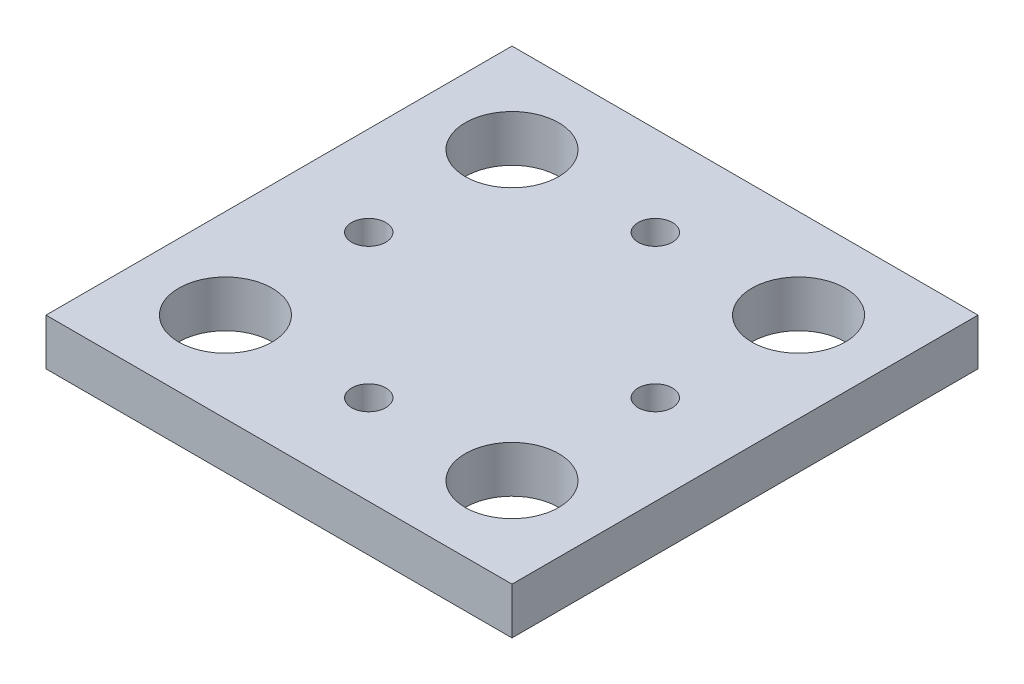
SolidWorks part; units mm, degrees
material "polylactic acid(PLA)(20%)"
ref_plane "Front Plane" through (0, 0, 0) normal (0, 0, 1) x (1, 0, 0)
ref_plane "Top Plane" through (0, 0, 0) normal (0, 1, 0) x (1, 0, 0)
ref_plane "Right Plane" through (0, 0, 0) normal (1, 0, 0) x (0, 0, -1)
sketch "Sketch1" plane through (0, 0, 0) normal (0, 1, 0) x (1, 0, 0)
  line L1 (-50, 50) -> (50, 50)
  line L2 (-50, 50) -> (-50, -50)
  line L3 (-50, -50) -> (50, -50)
  line L4 (50, 50) -> (50, -50)
  point P4 (50, 0)
  point P7 (0, -50)
  dimension "D1" = 100
extrude "Boss-Extrude1" add sketch "Sketch1" along normal blind 10
sketch "Sketch3" plane through (0, 0, 0) normal (0, 1, 0) x (1, 0, 0)
  line L0 (50, 50) -> (-50, 50) construction
  line L1 (-50, 50) -> (-50, -50) construction
  circle A0 centre (-30.7468, 30.7468) radius 10.025
  circle A1 centre (30.7468, 30.7468) radius 10.025
  circle A2 centre (30.7468, -30.7468) radius 10.025
  circle A3 centre (-30.7468, -30.7468) radius 10.025
  circle A4 centre (-30.7468, 30.7468) radius 19.2532 construction
  circle A5 centre (-30.7468, -30.7468) radius 19.2532 construction
  circle A6 centre (30.7468, 30.7468) radius 19.2532 construction
  circle A7 centre (0, 30.7468) radius 3.675
  circle A8 centre (0, 30.7468) radius 7.5 construction
  circle A9 centre (30.7468, 0) radius 3.675
  circle A10 centre (0, -30.7468) radius 3.675
  circle A11 centre (-30.7468, 0) radius 3.675
  point P14 (0, 0)
  point P29 (0, 0)
  dimension "D1" = 20.05
  dimension "D2" = 38.5064
  dimension "D4" = 7.35
  dimension "D5" = 15
  dimension "D3" = 4
  dimension "D6" = 4
extrude "Cut-Extrude3" cut sketch "Sketch3" against normal through all and the other way through all
